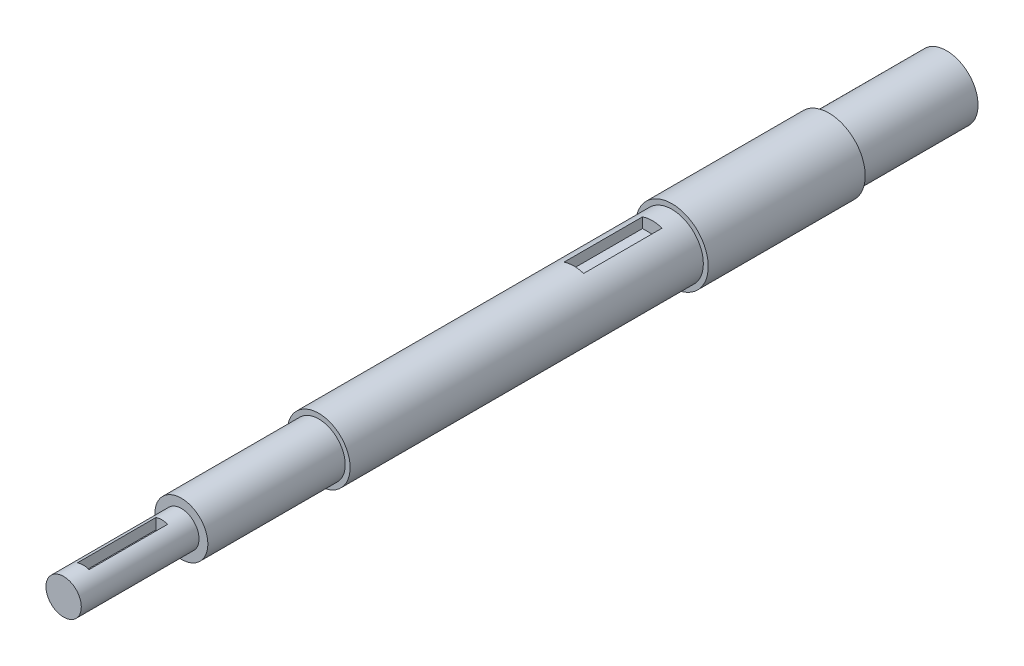
SolidWorks part; units mm, degrees
ref_plane "Front Plane" through (0, 0, 0) normal (0, 0, 1) x (1, 0, 0)
ref_plane "Top Plane" through (0, 0, 0) normal (0, 1, 0) x (1, 0, 0)
ref_plane "Right Plane" through (0, 0, 0) normal (1, 0, 0) x (0, 0, -1)
sketch "Sketch1" plane through (0, 0, 0) normal (0, 0, 1) x (1, 0, 0)
  circle A0 centre (0, 0) radius 9.25
  dimension "D1" = 18.5
extrude "Boss-Extrude1" add sketch "Sketch1" along normal blind 40
sketch "Sketch2" plane through (0, 0, 40) normal (0, 0, 1) x (1, 0, 0)
  circle A0 centre (0, 0) radius 8
  dimension "D1" = 16
extrude "Boss-Extrude2" add sketch "Sketch2" along normal blind 90
sketch "Sketch3" plane through (0, 0, 0) normal (0, 0, -1) x (-1, 0, 0)
  circle A0 centre (0, 0) radius 8
extrude "Boss-Extrude3" add sketch "Sketch3" along normal blind 30
sketch "Sketch4" plane through (0, 0, 130) normal (0, 0, 1) x (1, 0, 0)
  circle A0 centre (0, 0) radius 6.75
  dimension "D1" = 13.5
extrude "Boss-Extrude4" add sketch "Sketch4" along normal blind 35
sketch "Sketch5" plane through (0, 0, 165) normal (0, 0, 1) x (1, 0, 0)
  circle A0 centre (0, 0) radius 4.5
extrude "Boss-Extrude5" add sketch "Sketch5" along normal blind 30
sketch "Sketch6" plane through (0, 0, 195) normal (0, 0, 1) x (1, 0, 0)
  line L1 (-1.5, 7.5) -> (1.5, 7.5)
  line L2 (-1.5, 7.5) -> (-1.5, 1.5)
  line L3 (-1.5, 1.5) -> (1.5, 1.5)
  line L4 (1.5, 7.5) -> (1.5, 1.5)
  line L5 (-1.5, 7.5) -> (1.5, 1.5) construction
  line L6 (-1.5, 1.5) -> (1.5, 7.5) construction
  circle A0 centre (0, 0) radius 4.5 construction
  point P0 (0, 4.5)
  dimension "D1" = 6
  dimension "D2" = 3
extrude "Cut-Extrude1" cut sketch "Sketch6" against normal blind 20 from offset 5 offset against normal yes
sketch "Sketch7" plane through (0, 0, 130) normal (0, 0, 1) x (1, 0, 0)
  line L1 (-2.5, 11) -> (2.5, 11)
  line L2 (-2.5, 11) -> (-2.5, 5)
  line L3 (-2.5, 5) -> (2.5, 5)
  line L4 (2.5, 11) -> (2.5, 5)
  line L5 (-2.5, 11) -> (2.5, 5) construction
  line L6 (-2.5, 5) -> (2.5, 11) construction
  circle A0 centre (0, 0) radius 8 construction
  circle A1 centre (0, 0) radius 8 construction
  point P0 (0, 8)
  dimension "D1" = 6
  dimension "D2" = 5
extrude "Cut-Extrude2" cut sketch "Sketch7" against normal blind 20 from offset 65 offset against normal yes
sketch "Sketch8" plane through (0, 0, 195) normal (0, 0, 1) x (1, 0, 0)
  circle A0 centre (0, 0) radius 4.5
